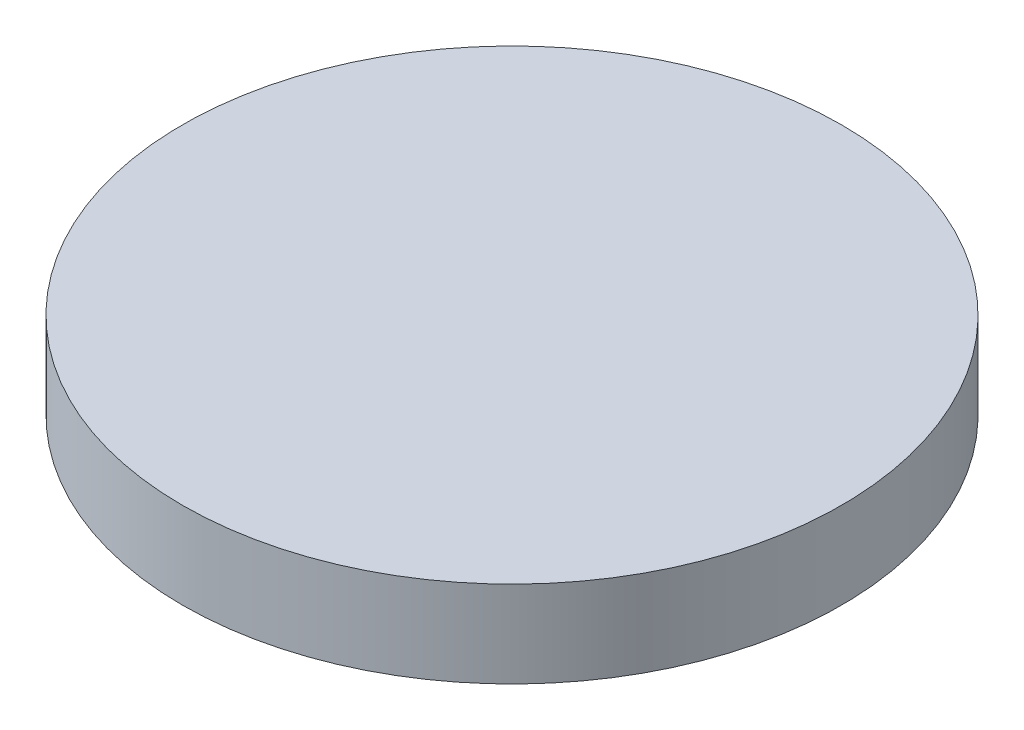
SolidWorks part; units mm, degrees
ref_plane "Front Plane" through (0, 0, 0) normal (0, 0, 1) x (1, 0, 0)
ref_plane "Top Plane" through (0, 0, 0) normal (0, 1, 0) x (1, 0, 0)
ref_plane "Right Plane" through (0, 0, 0) normal (1, 0, 0) x (0, 0, -1)
sketch "Sketch1" plane through (0, 0, 0) normal (0, 1, 0) x (1, 0, 0)
  circle A0 centre (0, 0) radius 76.2
  dimension "D1" = 152.4
extrude "Boss-Extrude1" add sketch "Sketch1" along normal blind 20
